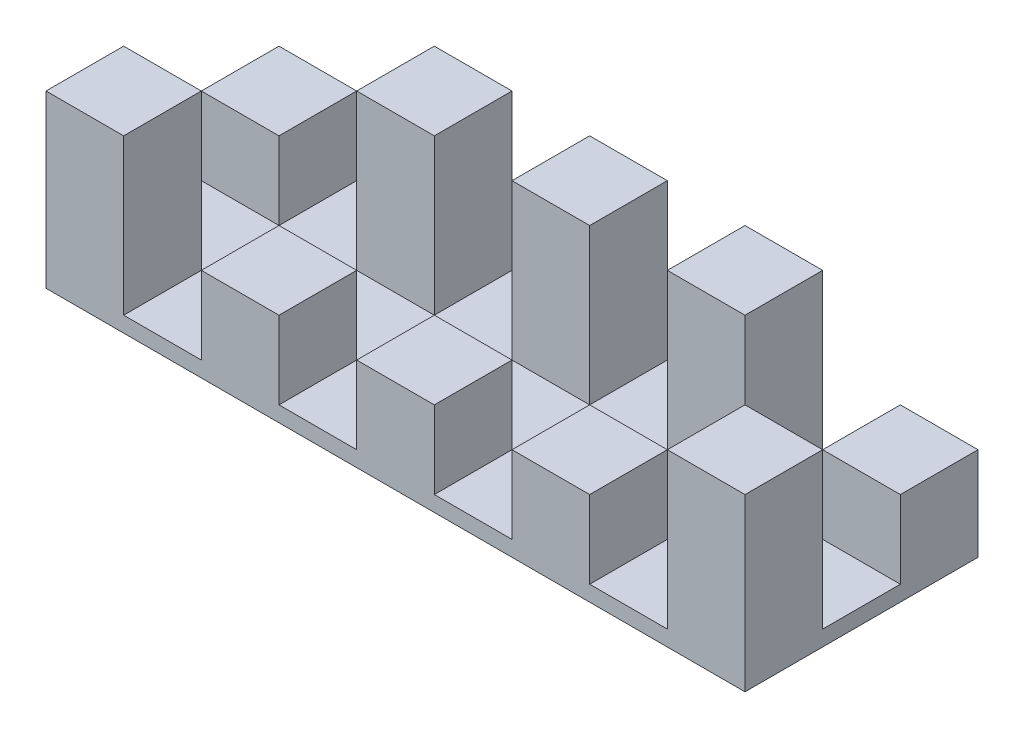
SolidWorks part; units mm, degrees
ref_plane "Front Plane" through (0, 0, 0) normal (0, 0, 1) x (1, 0, 0)
ref_plane "Top Plane" through (0, 0, 0) normal (0, 1, 0) x (1, 0, 0)
ref_plane "Right Plane" through (0, 0, 0) normal (1, 0, 0) x (0, 0, -1)
sketch "Sketch1" plane through (0, 0, 0) normal (0, 1, 0) x (1, 0, 0)
  line L1 (0, 0) -> (450, 0)
  line L2 (0, 0) -> (0, 150)
  line L3 (0, 150) -> (450, 150)
  line L4 (450, 0) -> (450, 150)
  dimension "D1" = 450
  dimension "D2" = 150
extrude "Boss-Extrude1" add sketch "Sketch1" along normal blind 10
sketch "Sketch2" plane through (0, 10, 0) normal (0, 1, 0) x (1, 0, 0)
  line L0 (100, 0) -> (100, 50)
  line L1 (0, 0) -> (50, 0)
  line L2 (0, 0) -> (0, 50)
  line L3 (0, 50) -> (50, 50)
  line L4 (50, 0) -> (50, 50)
  line L5 (100, 0) -> (150, 0)
  line L6 (150, 0) -> (150, 50)
  line L7 (100, 50) -> (150, 50)
  line L8 (200, 0) -> (200, 50)
  line L9 (200, 0) -> (250, 0)
  line L10 (250, 0) -> (250, 50)
  line L11 (200, 50) -> (250, 50)
  line L12 (300, 0) -> (300, 50)
  line L13 (300, 0) -> (350, 0)
  line L14 (350, 0) -> (350, 50)
  line L15 (300, 50) -> (350, 50)
  line L16 (400, 0) -> (400, 50)
  line L17 (400, 0) -> (450, 0)
  line L18 (450, 0) -> (450, 50)
  line L19 (400, 50) -> (450, 50)
  line L20 (100, 100) -> (100, 150)
  line L21 (100, 100) -> (150, 100)
  line L22 (150, 100) -> (150, 150)
  line L23 (100, 150) -> (150, 150)
  line L24 (200, 100) -> (200, 150)
  line L25 (200, 100) -> (250, 100)
  line L26 (250, 100) -> (250, 150)
  line L27 (200, 150) -> (250, 150)
  line L28 (300, 100) -> (300, 150)
  line L29 (300, 100) -> (350, 100)
  line L30 (350, 100) -> (350, 150)
  line L31 (300, 150) -> (350, 150)
  line L32 (400, 100) -> (400, 150)
  line L33 (400, 100) -> (450, 100)
  line L34 (450, 100) -> (450, 150)
  line L35 (400, 150) -> (450, 150)
  line L36 (0, 100) -> (0, 150)
  line L37 (0, 100) -> (50, 100)
  line L38 (50, 100) -> (50, 150)
  line L39 (0, 150) -> (50, 150)
  line L40 (0, 0) -> (100, 0) construction
  line L41 (0, 0) -> (0, 100) construction
  line L42 (0, 150) -> (0, 0) construction
  line M42 (0, 150) -> (0, 0)
  line M43 (0, 0) -> (450, 0)
  line M44 (450, 0) -> (450, 150)
  line M45 (450, 150) -> (0, 150)
  dimension "D1" = 50
  dimension "D2" = 50
  dimension "D5" = 100
  dimension "D6" = 100
  dimension "D3" = 5
  dimension "D4" = 2
extrude "Boss-Extrude2" add sketch "Sketch2" along normal blind 50 contours L7 L0 L6 M43 | L11 L8 L10 M43 | L15 L12 L14 M43 | L32 L33 M44 M45 | L37 L38 M45 M42
sketch "Sketch5" plane through (0, 10, 0) normal (0, 1, 0) x (1, 0, 0)
  line L0 (-141.409, 75) -> (510.2005, 75) construction
  line L2 (0, 0) -> (100, 0) construction
  line L3 (400, 150) -> (400, 100) construction
  line L4 (400, 100) -> (450, 100) construction
  line L5 (450, 100) -> (450, 150) construction
  line L6 (450, 150) -> (400, 150) construction
  line L7 (0, 100) -> (50, 100) construction
  line L8 (50, 100) -> (50, 150) construction
  line L9 (50, 150) -> (0, 150) construction
  line L10 (0, 150) -> (0, 100) construction
  line L11 (350, 50) -> (300, 50) construction
  line L12 (300, 50) -> (300, 0) construction
  line L13 (300, 0) -> (350, 0) construction
  line L14 (350, 0) -> (350, 50) construction
  line L15 (250, 50) -> (200, 50) construction
  line L16 (200, 50) -> (200, 0) construction
  line L17 (200, 0) -> (250, 0) construction
  line L18 (250, 0) -> (250, 50) construction
  line L19 (150, 50) -> (100, 50) construction
  line L20 (100, 50) -> (100, 0) construction
  line L21 (100, 0) -> (150, 0) construction
  line L22 (150, 0) -> (150, 50) construction
  line L23 (400, 150) -> (400, 100)
  line L24 (400, 100) -> (450, 100)
  line L25 (450, 100) -> (450, 150)
  line L26 (450, 150) -> (400, 150)
  line L27 (0, 100) -> (50, 100)
  line L28 (50, 100) -> (50, 150)
  line L29 (50, 150) -> (0, 150)
  line L30 (0, 150) -> (0, 100)
  line L31 (350, 50) -> (300, 50)
  line L32 (300, 50) -> (300, 0)
  line L33 (300, 0) -> (350, 0)
  line L34 (350, 0) -> (350, 50)
  line L35 (250, 50) -> (200, 50)
  line L36 (200, 50) -> (200, 0)
  line L37 (200, 0) -> (250, 0)
  line L38 (250, 0) -> (250, 50)
  line L39 (150, 50) -> (100, 50)
  line L40 (100, 50) -> (100, 0)
  line L41 (100, 0) -> (150, 0)
  line L42 (150, 0) -> (150, 50)
  line L43 (450, 0) -> (400, 0)
  line L44 (450, 50) -> (450, 0)
  line L45 (400, 50) -> (450, 50)
  line L46 (400, 0) -> (400, 50)
  line L47 (0, 0) -> (0, 50)
  line L48 (50, 0) -> (0, 0)
  line L49 (50, 50) -> (50, 0)
  line L50 (0, 50) -> (50, 50)
  line L51 (250, 150) -> (250, 100)
  line L52 (200, 150) -> (250, 150)
  line L53 (200, 100) -> (200, 150)
  line L54 (250, 100) -> (200, 100)
  line L55 (350, 150) -> (350, 100)
  line L56 (300, 150) -> (350, 150)
  line L57 (300, 100) -> (300, 150)
  line L58 (350, 100) -> (300, 100)
  line L59 (100, 150) -> (150, 150)
  line L60 (100, 100) -> (100, 150)
  line L61 (150, 150) -> (150, 100)
  line L62 (150, 100) -> (100, 100)
  point P4 (-141.409, 69.7379)
  line M11 (0, 100) -> (0, 0)
  line M12 (0, 0) -> (100, 0)
  line M24 (350, 0) -> (450, 0)
  line M25 (450, 0) -> (450, 100)
  line M28 (400, 150) -> (50, 150)
  dimension "D1" = 75
extrude "Boss-Extrude3" add sketch "Sketch5" along normal blind 100 contours L50 L49 M11 M12 | L62 L61 L60 M28 | L54 L51 L53 M28 | L46 L45 M24 M25 | L55 L58 L57 L56
